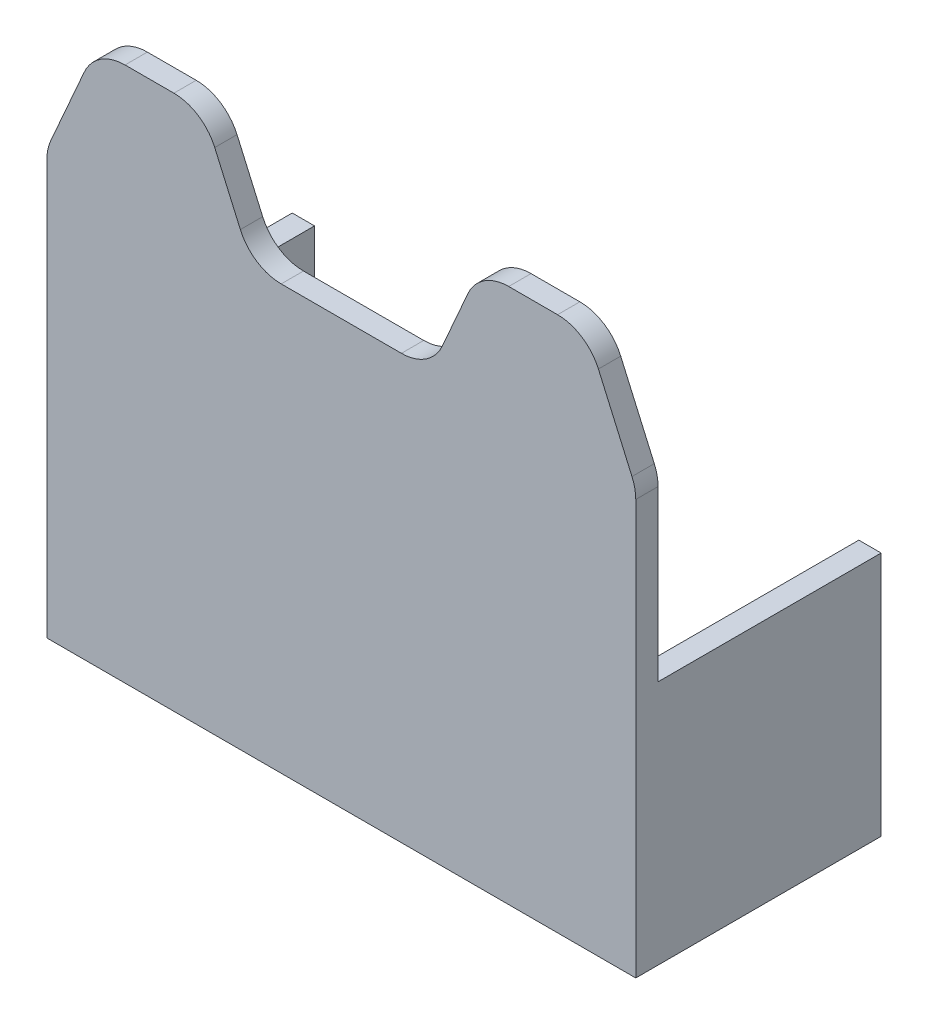
SolidWorks part; units mm, degrees
ref_plane "前视基准面" through (0, 0, 0) normal (0, 0, 1) x (1, 0, 0)
ref_plane "上视基准面" through (0, 0, 0) normal (0, 1, 0) x (1, 0, 0)
ref_plane "右视基准面" through (0, 0, 0) normal (1, 0, 0) x (0, 0, -1)
sketch "草图1" plane through (0, 0, 0) normal (0, 0, 1) x (1, 0, 0)
  line L0 (-66, 30) -> (66, 30)
  line L1 (-61, 25) -> (61, 25)
  line L2 (-61, 25) -> (-61, -25)
  line L4 (61, 25) -> (61, -25)
  line L5 (-61, 25) -> (61, -25) construction
  line L6 (-61, -25) -> (61, 25) construction
  line L7 (66, 30) -> (66, -25)
  line L9 (-66, 30) -> (-66, -25)
  line L10 (-61, -25) -> (-66, -25)
  line L11 (61, -25) -> (66, -25)
  line L12 (66, 30) -> (66, -30) construction
  line L13 (-66, 30) -> (-66, -30) construction
  line L14 (-66, -30) -> (66, -30) construction
  line L15 (-61, -25) -> (61, -25) construction
  point P0 (0, 0)
  dimension "D1" = 122
  dimension "D2" = 50
  dimension "D3" = 5
extrude "凸台-拉伸1" add sketch "草图1" along normal blind 50
sketch "草图2" plane through (0, 0, 0) normal (0, 0, 1) x (1, 0, 0)
  line L0 (-61, -25) -> (-61, 25) construction
  line L1 (-61, -13) -> (-53.5, -13)
  line L2 (-61, -13) -> (-61, -25)
  line L3 (-61, -25) -> (-53.5, -25)
  line L6 (61, -25) -> (53.5, -25)
  line L7 (61, -25) -> (61, -13)
  line L8 (61, -13) -> (53.5, -13)
  arc A0 (-53.5, -13) -> (-53.5, -25) centre (-53.5, -19) cw
  arc A1 (53.5, -25) -> (53.5, -13) centre (53.5, -19) cw
  circle A2 centre (-53.5, -19) radius 2.5
  circle A3 centre (53.5, -19) radius 2.5
  dimension "D5" = 5
  dimension "D6" = 5
  dimension "D1" = 12
  dimension "D2" = 12
  dimension "D3" = 7.5
  dimension "D4" = 7.5
extrude "凸台-拉伸2" add sketch "草图2" along normal blind 5
sketch "草图6" plane through (0, 0, 5) normal (0, 0, 1) x (1, 0, 0)
  line L1 (-49.7472, -19) -> (-51.6236, -15.75)
  line L2 (-51.6236, -15.75) -> (-55.3764, -15.75)
  line L3 (-55.3764, -15.75) -> (-57.2528, -19)
  line L4 (-57.2528, -19) -> (-55.3764, -22.25)
  line L5 (-55.3764, -22.25) -> (-51.6236, -22.25)
  line L6 (-51.6236, -22.25) -> (-49.7472, -19)
  line L7 (57.2528, -19) -> (55.3764, -15.75)
  line L8 (55.3764, -15.75) -> (51.6236, -15.75)
  line L9 (51.6236, -15.75) -> (49.7472, -19)
  line L10 (49.7472, -19) -> (51.6236, -22.25)
  line L11 (51.6236, -22.25) -> (55.3764, -22.25)
  line L12 (55.3764, -22.25) -> (57.2528, -19)
  circle A0 centre (-53.5, -19) radius 3.25 construction
  circle A1 centre (53.5, -19) radius 3.25 construction
  dimension "D1" = 6.5
  dimension "D2" = 6.5
extrude "切除-拉伸2" cut sketch "草图6" against normal blind 2
sketch "草图7" plane through (0, 0, 50) normal (0, 0, 1) x (1, 0, 0)
  line L1 (-66, 30) -> (66, 30)
  line L2 (-66, 30) -> (-66, -25)
  line L3 (-66, -25) -> (66, -25)
  line L4 (66, 30) -> (66, -25)
extrude "凸台-拉伸3" add sketch "草图7" along normal blind 5
sketch "草图8" plane through (0, 0, 0) normal (0, 0, -1) x (-1, 0, 0)
  line L0 (-61, 25) -> (-61, 30) construction
  line L1 (-66, 30) -> (66, 30) construction
  line L2 (61, 25) -> (61, 30) construction
  line L4 (-61, 25) -> (61, 25)
  line L5 (-61, 25) -> (-61, 30)
  line L6 (-61, 30) -> (61, 30)
  line L7 (61, 25) -> (61, 30)
extrude "切除-拉伸3" cut sketch "草图8" against normal blind 50
sketch "草图9" plane through (0, 0, 55) normal (0, 0, 1) x (1, 0, 0)
  line L1 (-66, 30) -> (66, 30)
  line L2 (-31, 95) -> (-20, 70)
  line L4 (66, 30) -> (66, 70)
  line L6 (-66, 30) -> (-66, 70)
  line L7 (-66, 70) -> (-55, 95)
  line L8 (-55, 95) -> (-31, 95)
  line L9 (55, 95) -> (66, 70)
  line L10 (-20, 70) -> (20, 70)
  line L11 (20, 70) -> (31, 95)
  line L12 (31, 95) -> (55, 95)
  dimension "D1" = 11
  dimension "D2" = 40
  dimension "D3" = 65
  dimension "D4" = 11
  dimension "D5" = 65
  dimension "D6" = 40
  dimension "D7" = 46
  dimension "D8" = 46
  dimension "D9" = 132
  dimension "D10" = 24
  dimension "D11" = 24
extrude "凸台-拉伸4" add sketch "草图9" against normal blind 5
fillet "圆角1" radius 10 1 edges at (-66, 70, 52.5)
fillet "圆角2" radius 10 1 edges at (-55, 95, 52.5)
fillet "圆角3" radius 10 1 edges at (66, 70, 52.5)
fillet "圆角4" radius 10 1 edges at (-31, 95, 52.5)
fillet "圆角5" radius 10 1 edges at (-20, 70, 52.5)
fillet "圆角6" radius 10 1 edges at (20, 70, 52.5)
fillet "圆角7" radius 10 1 edges at (31, 95, 52.5)
fillet "圆角8" radius 10 1 edges at (55, 95, 52.5)
